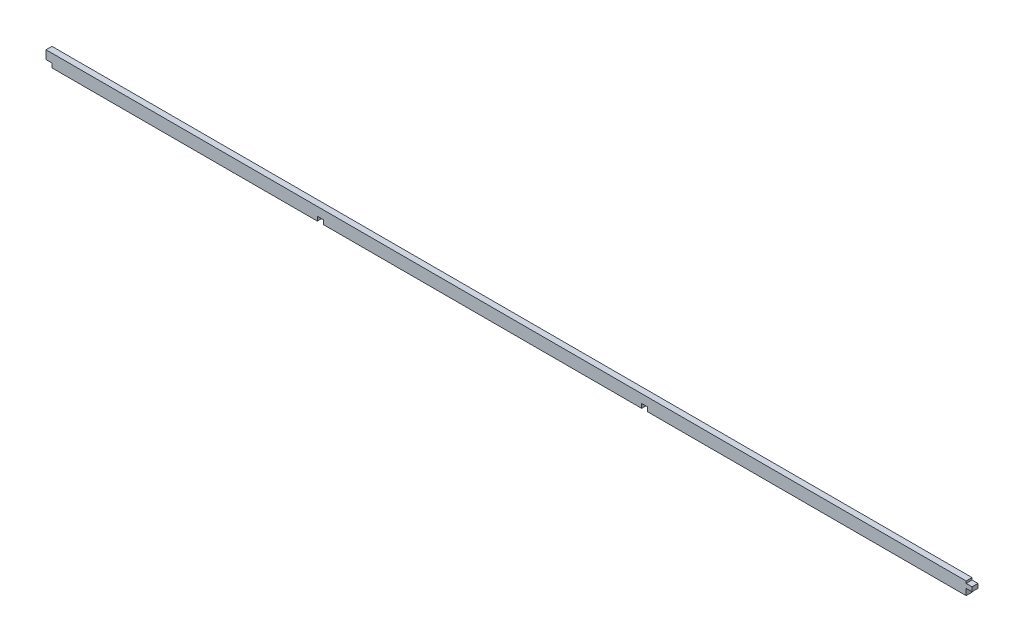
SolidWorks part; units mm, degrees
material "Фанера"
ref_plane "Front Plane" through (0, 0, 0) normal (0, 0, 1) x (1, 0, 0)
ref_plane "Top Plane" through (0, 0, 0) normal (0, 1, 0) x (1, 0, 0)
ref_plane "Right Plane" through (0, 0, 0) normal (1, 0, 0) x (0, 0, -1)
sketch "Эскиз1" plane through (0, 0, 0) normal (0, 0, 1) x (1, 0, 0)
  line L0 (0, -4) -> (2.8, -4)
  line L1 (2.8, -6) -> (127.8, -6)
  line L2 (0, -4) -> (0, 0)
  line L3 (0, 0) -> (433.4, 0)
  line L4 (127.8, 20.0008) -> (127.8, -17.954) construction
  line L5 (130.6, 18.2809) -> (130.6, -12.6588) construction
  line L6 (2.8, -4) -> (2.8, -6)
  line L7 (280.6, 21.1399) -> (280.6, -20.4716) construction
  line L8 (283.4, 21.1399) -> (283.4, -16.4614) construction
  line L9 (127.8, -6) -> (127.8, -4)
  line L10 (127.8, -4) -> (130.6, -4)
  line L11 (130.6, -4) -> (130.6, -6)
  line L12 (130.6, -6) -> (280.6, -6)
  line L13 (280.6, -6) -> (280.6, -4)
  line L14 (280.6, -4) -> (283.4, -4)
  line L15 (283.4, -4) -> (283.4, -6)
  line L16 (283.4, -6) -> (433.4, -6)
  line L17 (433.4, 0) -> (433.4, -1)
  line L18 (420.6815, -4) -> (449.0477, -4) construction
  line L19 (433.4, -3) -> (433.4, -6)
  line L20 (433.4, -3) -> (436.2, -3)
  line L22 (433.4, -1) -> (436.2, -1)
  line L23 (436.2, -3) -> (436.2, -1)
  line L24 (433.4, -2) -> (436.2, -1) construction
  line L25 (433.4, -2) -> (436.2, -3) construction
  point P26 (433.4, -2)
  dimension "D1" = 4
  dimension "D2" = 433.4
  dimension "D3" = 2.8
  dimension "D4" = 125
  dimension "D5" = 2.8
  dimension "D6" = 4
  dimension "D7" = 150
  dimension "D8" = 2.8
  dimension "D9" = 4
  dimension "D10" = 4
  dimension "D11" = 2
  dimension "D12" = 2
  dimension "D13" = 1
  dimension "D14" = 2.8
  dimension "D15" = 6
extrude "Бобышка-Вытянуть1" add sketch "Эскиз1" along normal mid plane 2.8
